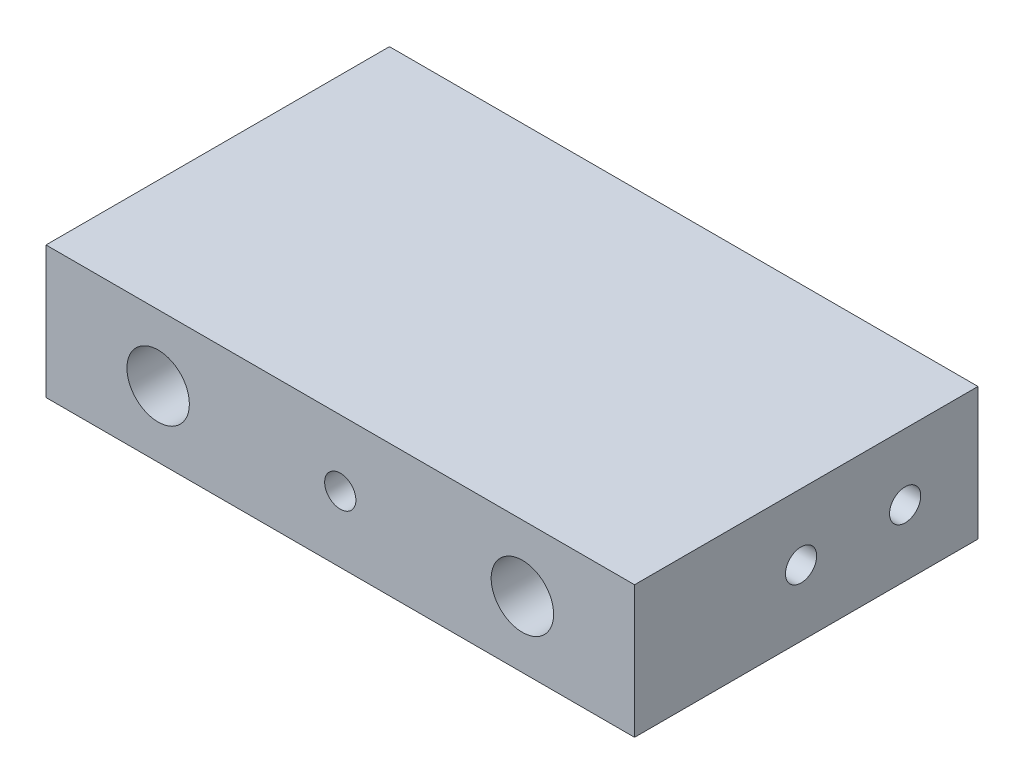
SolidWorks part; units mm, degrees
material "6061-T6 (SS)"
ref_plane "X-Y Datum" through (0, 0, 0) normal (0, 0, 1) x (1, 0, 0)
ref_plane "X-Z Datum" through (0, 0, 0) normal (0, 1, 0) x (1, 0, 0)
ref_plane "Y-Z Datum" through (0, 0, 0) normal (1, 0, 0) x (0, 0, -1)
sketch "Sketch1" plane through (0, 0, 0) normal (0, 0, 1) x (1, 0, 0)
  line L1 (-28.275, 6.35) -> (28.275, 6.35)
  line L2 (-28.275, 6.35) -> (-28.275, -6.35)
  line L3 (-28.275, -6.35) -> (28.275, -6.35)
  line L4 (28.275, 6.35) -> (28.275, -6.35)
  line L5 (-28.275, 6.35) -> (28.275, -6.35) construction
  line L6 (-28.275, -6.35) -> (28.275, 6.35) construction
  point P0 (0, 0)
  dimension "D1" = 56.55
  dimension "D2" = 12.7
extrude "Boss-Extrude1" add sketch "Sketch1" along normal blind 33 contours L2 L3 L4 L1
sketch "Sketch2" plane through (0, 0, 33) normal (0, 0, 1) x (1, 0, 0)
  line L0 (-28.275, 0) -> (28.275, 0) construction
  line L1 (-28.275, 6.35) -> (-28.275, -6.35) construction
  line L2 (28.275, 6.35) -> (28.275, -6.35) construction
  line L3 (-17.5, 0) -> (17.5, 0) construction
  circle A0 centre (17.5, 0) radius 3
  circle A1 centre (-17.5, 0) radius 3
  circle A2 centre (0, 0) radius 1.5
  point P10 (0, 0)
  dimension "D1" = 6
  dimension "D3" = 3
  dimension "D2" = 35
extrude "Cut-Extrude1" cut sketch "Sketch2" against normal blind 10 contours A1 L0 L3 | L0 A1 L3 | L0 L3 A0 | L3 L0 A0 | A2
sketch "Sketch3" plane through (-28.275, 0, 0) normal (-1, 0, 0) x (0, 0, 1)
  line L0 (33, 0) -> (0, 0) construction
  line L1 (33, 6.35) -> (33, -6.35) construction
  line L2 (0, 6.35) -> (0, -6.35) construction
  circle A0 centre (7, 0) radius 1.5
  circle A1 centre (17, 0) radius 1.5
  dimension "D1" = 3
  dimension "D2" = 10
  dimension "D3" = 7
extrude "Cut-Extrude2" cut sketch "Sketch3" against normal through all contours A0 L0 | L0 A0 | A1 L0 | L0 A1
